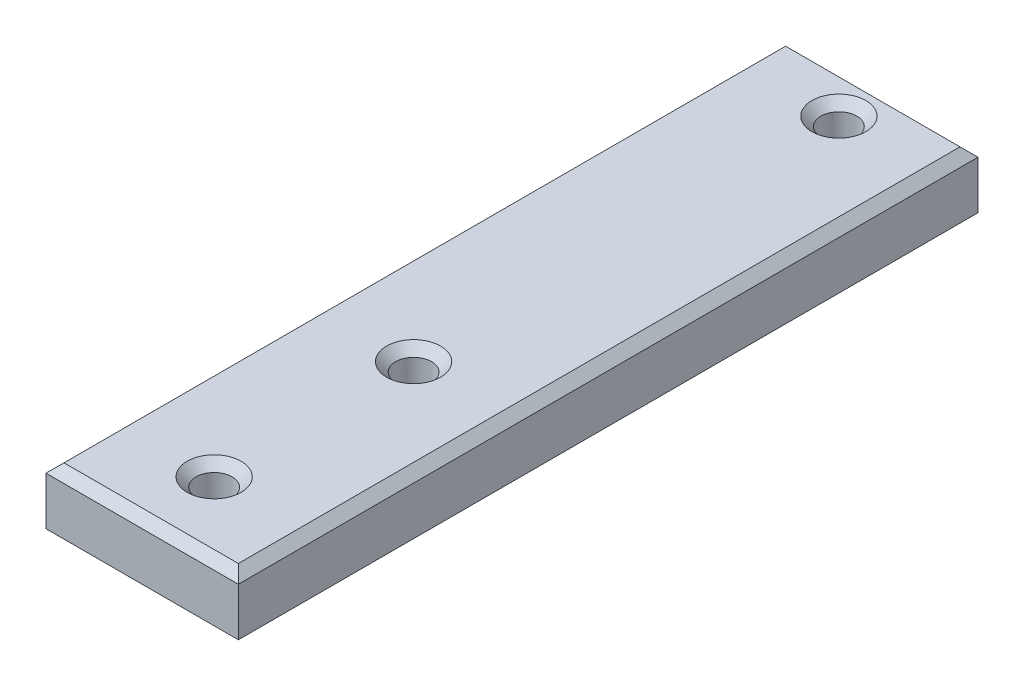
SolidWorks part; units mm, degrees
ref_plane "Front Plane" through (0, 0, 0) normal (0, 0, 1) x (1, 0, 0)
ref_plane "Top Plane" through (0, 0, 0) normal (0, 1, 0) x (1, 0, 0)
ref_plane "Right Plane" through (0, 0, 0) normal (1, 0, 0) x (0, 0, -1)
sketch "Sketch1" plane through (0, 0, 0) normal (0, 1, 0) x (1, 0, 0)
  line L0 (0, 0) -> (0, 37.725) construction
  line L1 (-10.6922, 47.275) -> (-10.6922, -34.95)
  line L2 (0, 18.8625) -> (-10.6922, 18.8625) construction
  line L3 (0, 37.725) -> (0, 47.275) construction
  line L4 (10.6922, -9.55) -> (-10.6922, -9.55) construction
  line L6 (10.6922, 47.275) -> (-10.6922, 47.275)
  line L8 (10.6922, -9.55) -> (-10.6922, 47.275) construction
  line L9 (10.6922, 47.275) -> (-10.6922, -9.55) construction
  line L10 (0, 42.5) -> (10.6922, 42.5) construction
  line L12 (-10.6922, -34.95) -> (10.6922, -34.95)
  line L14 (-10.6922, -26.95) -> (10.6922, -26.95) construction
  line L15 (10.6922, -34.95) -> (10.6922, 47.275)
  line L16 (0, -26.95) -> (0, -4.775) construction
  circle A0 centre (0, 42.5) radius 2
  circle A1 centre (0, -4.775) radius 2
  circle A2 centre (0, -26.95) radius 2
  dimension "D3" = 4
  dimension "D5" = 4
  dimension "D1" = 42.5
  dimension "D2" = 22.175
  dimension "D4" = 25.4
  dimension "D6" = 16
  dimension "D7" = 26.95
extrude "Boss-Extrude1" add sketch "Sketch1" along normal blind 6.35
chamfer "Chamfer1" distance 1 angle 45 7 edges at (0, 6.35, 2.775) (0, 6.35, -47.275) (0, 6.35, -40.5) (0, 6.35, 28.95) (10.6922, 6.35, -6.1625) (0, 6.35, 34.95) (-10.6922, 6.35, -6.1625)
